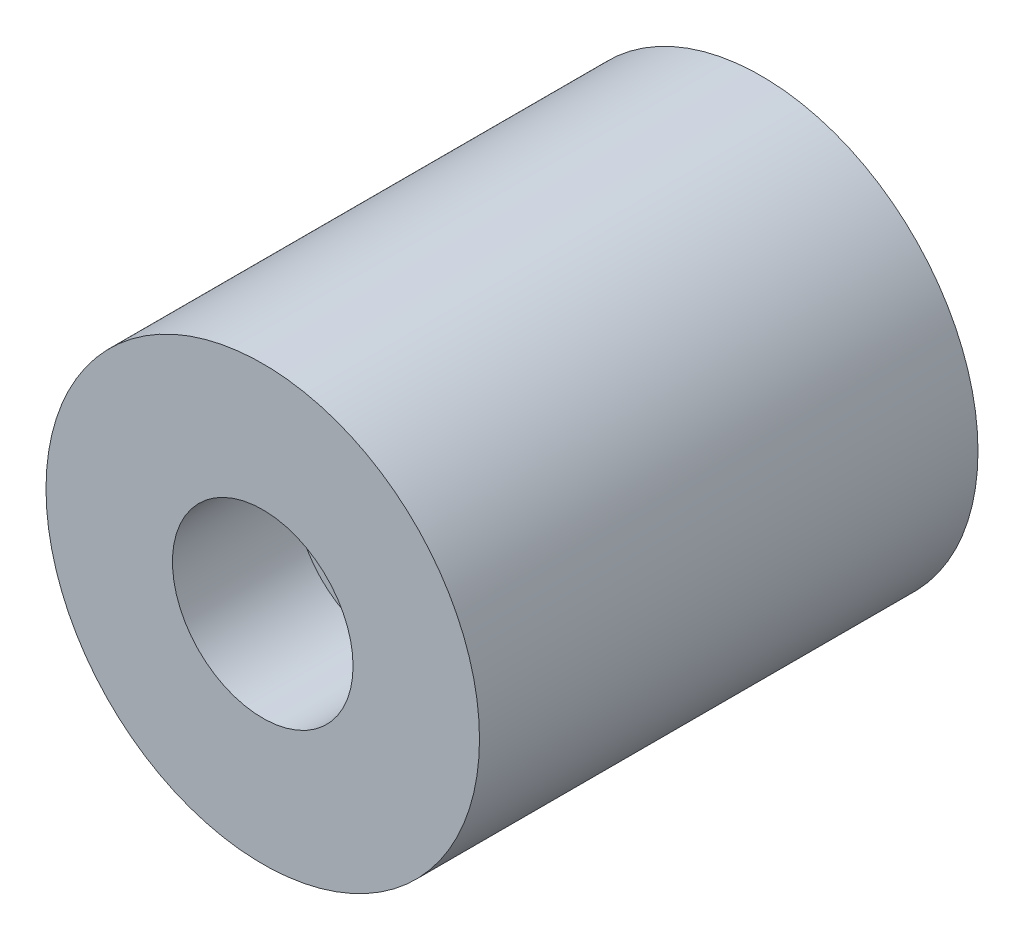
SolidWorks part; units mm, degrees
ref_plane "Front Plane" through (0, 0, 0) normal (0, 0, 1) x (1, 0, 0)
ref_plane "Top Plane" through (0, 0, 0) normal (0, 1, 0) x (1, 0, 0)
ref_plane "Right Plane" through (0, 0, 0) normal (1, 0, 0) x (0, 0, -1)
sketch "Sketch2" plane through (0, 0, 0) normal (0, 0, 1) x (1, 0, 0)
  circle A0 centre (0, 0) radius 30
extrude "Boss-Extrude2" add sketch "Sketch2" against normal blind 40.09
sketch "Sketch3" plane through (0, 0, 0) normal (0, 0, 1) x (1, 0, 0)
  circle A0 centre (0, 0) radius 30
sketch "Sketch4" plane through (0, 0, 0) normal (0, 0, 1) x (1, 0, 0)
  circle A0 centre (0, 0) radius 30
extrude "Boss-Extrude4" add sketch "Sketch4" along normal blind 27.91
sketch "Sketch5" plane through (0, 0, 27.91) normal (0, 0, 1) x (1, 0, 0)
  circle A0 centre (0, 0) radius 17.8886
sketch "Sketch6" plane through (0, 0, 27.91) normal (0, 0, 1) x (1, 0, 0)
  circle A0 centre (0, 0) radius 12.5
  dimension "D1" = 25
extrude "Cut-Extrude1" cut sketch "Sketch6" against normal blind 19
sketch "Sketch7" plane through (0, 0, 8.91) normal (0, 0, 1) x (1, 0, 0)
  circle A0 centre (0, 0) radius 9.25
  dimension "D1" = 18.5
extrude "Cut-Extrude2" cut sketch "Sketch7" against normal through all
sketch "Sketch8" plane through (0, 0, -40.09) normal (0, 0, -1) x (-1, 0, 0)
  circle A0 centre (0, 0) radius 9.25 construction
  circle A1 centre (0, 0) radius 30
  circle A2 centre (0, 0) radius 30
  circle A3 centre (0, 0) radius 9.25
  dimension "D1" = 0
extrude "Cut-Extrude3" cut sketch "Sketch8" against normal blind 1
sketch "Sketch9" plane through (0, 0, -39.09) normal (0, 0, -1) x (-1, 0, 0)
  circle A0 centre (0, 0) radius 9.25 construction
  circle A1 centre (0, 0) radius 30
  circle A2 centre (0, 0) radius 30
  circle A3 centre (0, 0) radius 9.25
  dimension "D1" = 0
extrude "Cut-Extrude4" cut sketch "Sketch9" against normal blind 1.21
sketch "Sketch10" plane through (0, 0, -37.88) normal (0, 0, -1) x (-1, 0, 0)
  circle A0 centre (0, 0) radius 30 construction
  circle A1 centre (0, 0) radius 30
extrude "Boss-Extrude5" add sketch "Sketch10" along normal blind 1
sketch "Sketch11" plane through (0, 0, -37.88) normal (0, 0, 1) x (1, 0, 0)
  circle A0 centre (0, 0) radius 9.25 construction
  circle A1 centre (0, 0) radius 9.25
extrude "Boss-Extrude6" add sketch "Sketch11" along normal blind 2
sketch "Sketch12" plane through (0, 0, -38.88) normal (0, 0, -1) x (-1, 0, 0)
  circle A0 centre (0, 0) radius 6.5
  dimension "D1" = 13
extrude "Boss-Extrude7" add sketch "Sketch12" along normal up to surface (7.206 mm away)
sketch "Sketch14" plane through (0, 0, -46.086) normal (0, 0, -1) x (-1, 0, 0)
  circle A0 centre (0, 0) radius 5
  circle A1 centre (0, 0) radius 6.5 construction
  circle A2 centre (0, 0) radius 6.5
  dimension "D1" = 10
extrude "Cut-Extrude5" cut sketch "Sketch14" against normal up to vertex (5 mm away)
sketch "Sketch15" plane through (0, 0, -35.88) normal (0, 0, 1) x (1, 0, 0)
  circle A0 centre (0, 0) radius 3.25
  dimension "D1" = 6.5
extrude "Cut-Extrude6" cut sketch "Sketch15" against normal through all
sketch "Sketch16" plane through (0, 0, -38.88) normal (0, 0, -1) x (-1, 0, 0)
  circle A0 centre (0, 0) radius 6.5 construction
  circle A1 centre (0, 0) radius 30
  circle A2 centre (0, 0) radius 30
  circle A3 centre (0, 0) radius 6.5
  dimension "D1" = 0
extrude "Boss-Extrude8" add sketch "Sketch16" along normal blind 0.21
sketch "Sketch17" plane through (0, 0, -39.09) normal (0, 0, -1) x (-1, 0, 0)
  circle A1 centre (0, 0) radius 30
  circle A2 centre (0, 0) radius 30
  circle A6 centre (0, 0) radius 6.5
  circle A7 centre (0, 0) radius 6.5
  dimension "D1" = 0
  dimension "D2" = 0
extrude "Boss-Extrude9" add sketch "Sketch17" along normal up to surface (1.996 mm away) up to face at (-5, 0, -41.086)
sketch "Sketch18" plane through (0, 0, -35.88) normal (0, 0, 1) x (1, 0, 0)
  circle A0 centre (0, 0) radius 9.25 construction
  circle A1 centre (0, 0) radius 3.25 construction
  circle A2 centre (0, 0) radius 9.25
  circle A3 centre (0, 0) radius 3.25
extrude "Boss-Extrude10" add sketch "Sketch18" along normal blind 0.79
sketch "Sketch19" plane through (0, 0, -35.09) normal (0, 0, 1) x (1, 0, 0)
  circle A0 centre (0, 0) radius 3.25 construction
  circle A1 centre (0, 0) radius 9.25
  circle A2 centre (0, 0) radius 9.25
  circle A3 centre (0, 0) radius 3.25
  dimension "D1" = 0
extrude "Cut-Extrude7" cut sketch "Sketch19" against normal blind 1
sketch "Sketch21" plane through (0, 0, 8.91) normal (0, 0, 1) x (1, 0, 0)
  circle A0 centre (0, 0) radius 9.25 construction
  circle A1 centre (0, 0) radius 12.5
  circle A2 centre (0, 0) radius 12.5
  circle A3 centre (0, 0) radius 9.25
  dimension "D1" = 0
extrude "Boss-Extrude11" add sketch "Sketch21" along normal blind 2
sketch "Sketch23" plane through (0, 0, 0) normal (0, 1, 0) x (1, 0, 0)
  line L0 (-30, -27.91) -> (-51.8079, -27.91) construction
  line L1 (-30, -27.91) -> (30, -27.91) construction
  line L2 (-30, 2.09) -> (-51.8079, 2.09) construction
  dimension "D1" = 30
